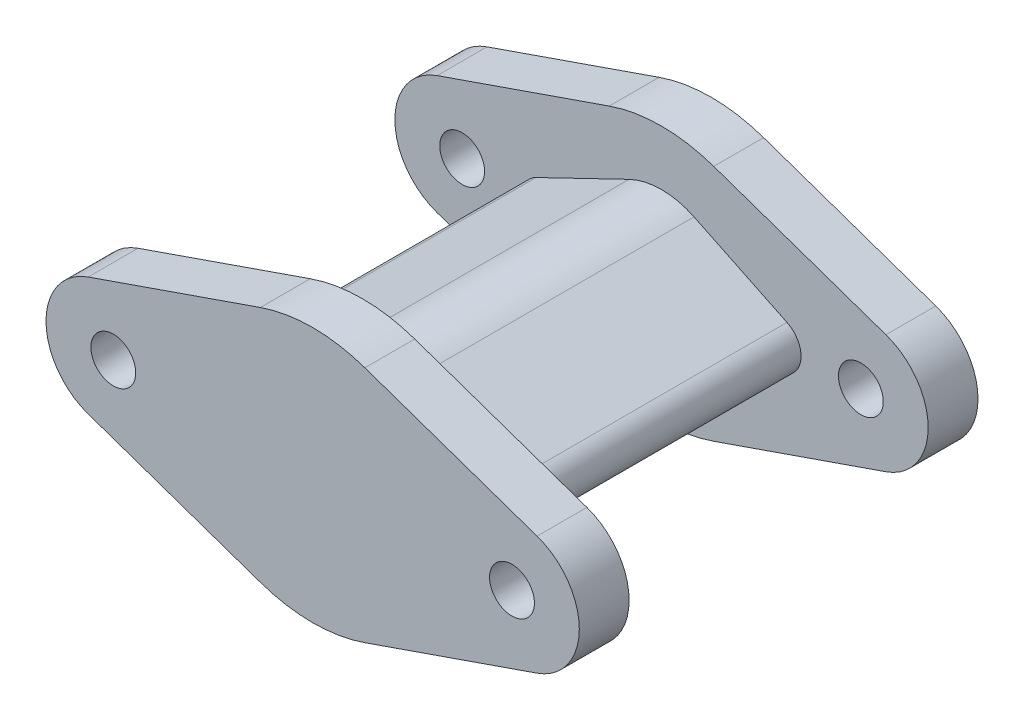
SolidWorks part; units mm, degrees
ref_plane "Front Plane" through (0, 0, 0) normal (0, 0, 1) x (1, 0, 0)
ref_plane "Top Plane" through (0, 0, 0) normal (0, 1, 0) x (1, 0, 0)
ref_plane "Right Plane" through (0, 0, 0) normal (1, 0, 0) x (0, 0, -1)
sketch "Sketch1" plane through (0, 0, 0) normal (0, 0, 1) x (1, 0, 0)
  line L4 (-39.6823, 0) -> (39.6823, 0) construction
  line L9 (0, -143.4641) -> (0, 143.4641) construction
  line L10 (-39.6823, 0) -> (0, 13.7593)
  line L11 (0, 13.7593) -> (39.6823, 0)
  line L12 (39.6823, 0) -> (0, -13.7593)
  line L13 (0, -13.7593) -> (-39.6823, 0)
  point P3 (0, 0)
  point P6 (0, 0)
  dimension "D1" = 42
  dimension "D2" = 26
  dimension "D3" = 42
extrude "Boss-Extrude1" add sketch "Sketch1" along normal blind 5
fillet "Fillet1" radius 6.3 1 edges at (39.6823, 0, 2.5)
fillet "Fillet2" radius 6.3 1 edges at (-39.6823, 0, 2.5)
fillet "Fillet3" radius 16 1 edges at (0, 13.7593, 2.5)
fillet "Fillet4" radius 16 1 edges at (0, -13.7593, 2.5)
sketch "Sketch2" plane through (0, 0, 5) normal (0, 0, 1) x (1, 0, 0)
  line L0 (0, 0) -> (-26.7516, 0) construction
  line L1 (0, 0) -> (0, -12.8248) construction
  circle A1 centre (0, 0) radius 12.8248
  arc A2 (-22.5155, 5.9523) -> (-22.5155, -5.9523) centre (-20.4516, 0) ccw construction
  circle A3 centre (-20, 0) radius 2.25
  circle A4 centre (20, 0) radius 2.25
  dimension "D1" = 25.6496
  dimension "D2" = 4.5
  dimension "D3" = 20
extrude "Cut-Extrude1" cut sketch "Sketch2" against normal through all contours A3 | A4
pattern_linear "LPattern3" count 2 spacing 35 along (0, 0, 1) of "Boss-Extrude1", "Fillet3", "Fillet2", "Fillet4", "Fillet1", "Cut-Extrude1"
sketch "Sketch3" plane through (0, 0, 5) normal (0, 0, 1) x (1, 0, 0)
  line L0 (0, -0.1892) -> (0, -7.6892) construction
  line L1 (0, -7.6892) -> (-7.5, -0.1892) construction
  line L2 (-7.5, -0.1892) -> (-11.5, -0.1892) construction
  line L3 (-3.2609, 6.5649) -> (-12.587, 2.0622)
  line L4 (-3.2609, -6.9432) -> (-12.587, -2.4405)
  line L5 (-3.2609, 6.5649) -> (-12.587, 2.0622)
  line L6 (-3.2609, -6.9432) -> (-12.587, -2.4405)
  line L7 (3.2609, -6.9432) -> (12.587, -2.4405)
  line L8 (3.2609, 6.5649) -> (12.587, 2.0622)
  arc A0 (-3.2609, -6.9432) -> (3.2609, -6.9432) centre (0, -0.1892) ccw
  arc A1 (-12.587, 2.0622) -> (-12.587, -2.4405) centre (-11.5, -0.1892) ccw
  arc A2 (12.587, 2.0622) -> (12.587, -2.4405) centre (11.5, -0.1892) cw
  arc A3 (3.2609, 6.5649) -> (-3.2609, 6.5649) centre (0, -0.1892) ccw
  dimension "D1" = 15
  dimension "D2" = 5
  dimension "D3" = 4
extrude "Boss-Extrude2" add sketch "Sketch3" along normal up to body separate body contours L4 A1 L3 A3 L8 A2 L7 A0
